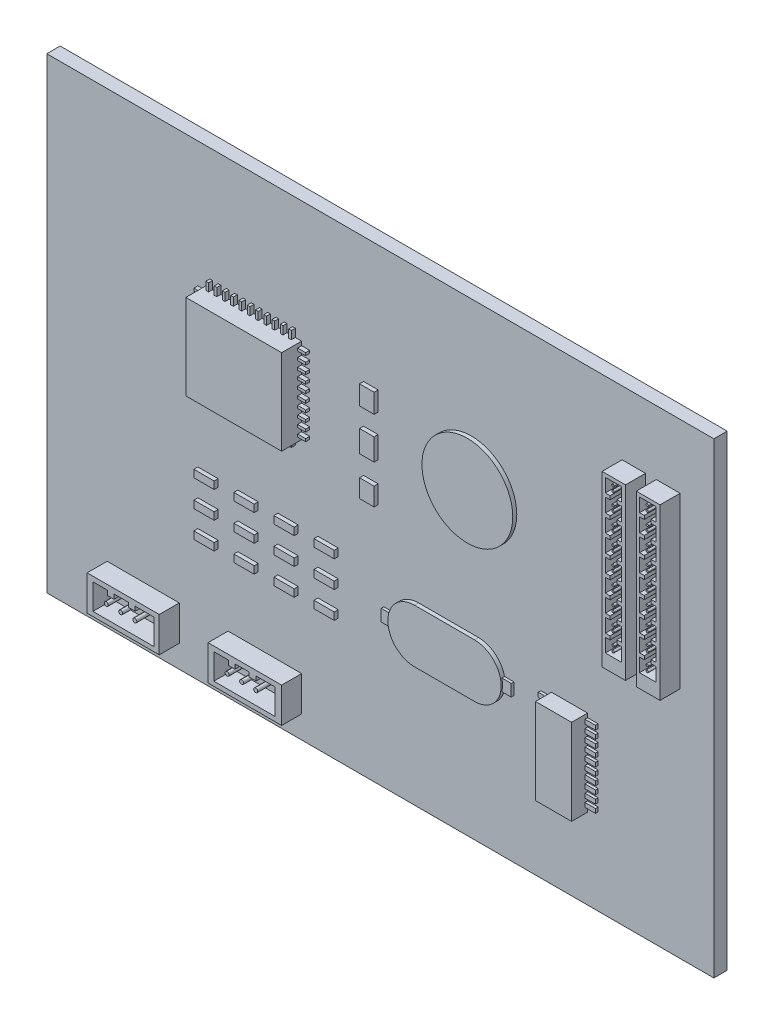
SolidWorks part; units mm, degrees
ref_plane "前视基准面" through (0, 0, 0) normal (0, 0, 1) x (1, 0, 0)
ref_plane "上视基准面" through (0, 0, 0) normal (0, 1, 0) x (1, 0, 0)
ref_plane "右视基准面" through (0, 0, 0) normal (1, 0, 0) x (0, 0, -1)
sketch "草图1" plane through (0, 0, 0) normal (0, 0, 1) x (1, 0, 0)
  line L1 (-25, 17.5) -> (25, 17.5)
  line L2 (-25, 17.5) -> (-25, -17.5)
  line L3 (-25, -17.5) -> (25, -17.5)
  line L4 (25, 17.5) -> (25, -17.5)
  line L5 (-25, 17.5) -> (25, -17.5) construction
  line L6 (-25, -17.5) -> (25, 17.5) construction
  point P0 (0, 0)
  point P5 (25, 0)
  dimension "D1" = 35
  dimension "D2" = 50
extrude "凸台-拉伸1" add sketch "草图1" along normal blind 1
sketch "草图2" plane through (0, 0, 1) normal (0, 0, 1) x (1, 0, 0)
  line L1 (-13.0751, 8.3934) -> (-5.8986, 8.3934)
  line L2 (-13.0751, 8.3934) -> (-13.0751, 1.997)
  line L3 (-13.0751, 1.997) -> (-5.8986, 1.997)
  line L4 (-5.8986, 8.3934) -> (-5.8986, 1.997)
  line L5 (-13.0751, 8.3934) -> (-5.8986, 1.997) construction
  line L6 (-13.0751, 1.997) -> (-5.8986, 8.3934) construction
  line L7 (-20.4774, -13.1874) -> (-15.0714, -13.1874)
  line L8 (-20.4774, -13.1874) -> (-20.4774, -15.8086)
  line L9 (-20.4774, -15.8086) -> (-15.0714, -15.8086)
  line L10 (-15.0714, -13.1874) -> (-15.0714, -15.8086)
  line L11 (-11.4127, -13.1874) -> (-5.8986, -13.1874)
  line L12 (-11.4127, -13.1874) -> (-11.4127, -15.8086)
  line L13 (-11.4127, -15.8086) -> (-5.8986, -15.8086)
  line L14 (-5.8986, -13.1874) -> (-5.8986, -15.8086)
  line L15 (18.1224, 12.6986) -> (19.8759, 12.6986)
  line L16 (18.1224, 12.6986) -> (18.1224, 0)
  line L17 (18.1224, 0) -> (19.8759, 0)
  line L18 (19.8759, 12.6986) -> (19.8759, 0)
  line L19 (20.6852, 12.6986) -> (22.4661, 12.6986)
  line L20 (20.6852, 12.6986) -> (20.6852, 0)
  line L21 (20.6852, 0) -> (22.4661, 0)
  line L22 (22.4661, 12.6986) -> (22.4661, 0)
  point P0 (-9.4869, 5.1952)
extrude "凸台-拉伸2" add sketch "草图2" along normal blind 1.5
sketch "草图3" plane through (0, 0, 1) normal (0, 0, 1) x (1, 0, 0)
  line L0 (-5.8986, 8.3934) -> (-13.0751, 8.3934) construction
  line L1 (-12.7751, 8.3934) -> (-12.5751, 8.3934)
  line L2 (-12.7751, 8.3934) -> (-12.7751, 8.9934)
  line L3 (-12.7751, 8.9934) -> (-12.5751, 8.9934)
  line L4 (-12.5751, 8.3934) -> (-12.5751, 8.9934)
  line L5 (-13.0751, 8.3934) -> (-13.0751, 1.997) construction
  line L6 (-12.1551, 8.9934) -> (-11.9551, 8.9934)
  line L7 (-12.1551, 8.3934) -> (-12.1551, 8.9934)
  line L8 (-11.9551, 8.3934) -> (-11.9551, 8.9934)
  line L9 (-12.1551, 8.3934) -> (-11.9551, 8.3934)
  line L10 (-11.5351, 8.9934) -> (-11.3351, 8.9934)
  line L11 (-11.5351, 8.3934) -> (-11.5351, 8.9934)
  line L12 (-11.3351, 8.3934) -> (-11.3351, 8.9934)
  line L13 (-11.5351, 8.3934) -> (-11.3351, 8.3934)
  line L14 (-10.9151, 8.9934) -> (-10.7151, 8.9934)
  line L15 (-10.9151, 8.3934) -> (-10.9151, 8.9934)
  line L16 (-10.7151, 8.3934) -> (-10.7151, 8.9934)
  line L17 (-10.9151, 8.3934) -> (-10.7151, 8.3934)
  line L18 (-10.2951, 8.9934) -> (-10.0951, 8.9934)
  line L19 (-10.2951, 8.3934) -> (-10.2951, 8.9934)
  line L20 (-10.0951, 8.3934) -> (-10.0951, 8.9934)
  line L21 (-10.2951, 8.3934) -> (-10.0951, 8.3934)
  line L22 (-9.6751, 8.9934) -> (-9.4751, 8.9934)
  line L23 (-9.6751, 8.3934) -> (-9.6751, 8.9934)
  line L24 (-9.4751, 8.3934) -> (-9.4751, 8.9934)
  line L25 (-9.6751, 8.3934) -> (-9.4751, 8.3934)
  line L26 (-9.0551, 8.9934) -> (-8.8551, 8.9934)
  line L27 (-9.0551, 8.3934) -> (-9.0551, 8.9934)
  line L28 (-8.8551, 8.3934) -> (-8.8551, 8.9934)
  line L29 (-9.0551, 8.3934) -> (-8.8551, 8.3934)
  line L30 (-8.4351, 8.9934) -> (-8.2351, 8.9934)
  line L31 (-8.4351, 8.3934) -> (-8.4351, 8.9934)
  line L32 (-8.2351, 8.3934) -> (-8.2351, 8.9934)
  line L33 (-8.4351, 8.3934) -> (-8.2351, 8.3934)
  line L34 (-7.8151, 8.9934) -> (-7.6151, 8.9934)
  line L35 (-7.8151, 8.3934) -> (-7.8151, 8.9934)
  line L36 (-7.6151, 8.3934) -> (-7.6151, 8.9934)
  line L37 (-7.8151, 8.3934) -> (-7.6151, 8.3934)
  line L38 (-7.1951, 8.9934) -> (-6.9951, 8.9934)
  line L39 (-7.1951, 8.3934) -> (-7.1951, 8.9934)
  line L40 (-6.9951, 8.3934) -> (-6.9951, 8.9934)
  line L41 (-7.1951, 8.3934) -> (-6.9951, 8.3934)
  line L42 (-6.5751, 8.9934) -> (-6.3751, 8.9934)
  line L43 (-6.5751, 8.3934) -> (-6.5751, 8.9934)
  line L44 (-6.3751, 8.3934) -> (-6.3751, 8.9934)
  line L45 (-6.5751, 8.3934) -> (-6.3751, 8.3934)
  line L46 (-5.8986, 5.1952) -> (-4.9719, 5.1952) construction
  line L47 (-5.8986, 1.997) -> (-5.8986, 8.3934) construction
  line L48 (-6.5751, 1.997) -> (-6.3751, 1.997)
  line L49 (-6.3751, 1.997) -> (-6.3751, 1.397)
  line L50 (-6.5751, 1.997) -> (-6.5751, 1.397)
  line L51 (-6.5751, 1.397) -> (-6.3751, 1.397)
  line L52 (-7.1951, 1.997) -> (-6.9951, 1.997)
  line L53 (-6.9951, 1.997) -> (-6.9951, 1.397)
  line L54 (-7.1951, 1.997) -> (-7.1951, 1.397)
  line L55 (-7.1951, 1.397) -> (-6.9951, 1.397)
  line L56 (-7.8151, 1.997) -> (-7.6151, 1.997)
  line L57 (-7.6151, 1.997) -> (-7.6151, 1.397)
  line L58 (-7.8151, 1.997) -> (-7.8151, 1.397)
  line L59 (-7.8151, 1.397) -> (-7.6151, 1.397)
  line L60 (-8.4351, 1.997) -> (-8.2351, 1.997)
  line L61 (-8.2351, 1.997) -> (-8.2351, 1.397)
  line L62 (-8.4351, 1.997) -> (-8.4351, 1.397)
  line L63 (-8.4351, 1.397) -> (-8.2351, 1.397)
  line L64 (-9.0551, 1.997) -> (-8.8551, 1.997)
  line L65 (-8.8551, 1.997) -> (-8.8551, 1.397)
  line L66 (-9.0551, 1.997) -> (-9.0551, 1.397)
  line L67 (-9.0551, 1.397) -> (-8.8551, 1.397)
  line L68 (-9.6751, 1.997) -> (-9.4751, 1.997)
  line L69 (-9.4751, 1.997) -> (-9.4751, 1.397)
  line L70 (-9.6751, 1.997) -> (-9.6751, 1.397)
  line L71 (-9.6751, 1.397) -> (-9.4751, 1.397)
  line L72 (-10.2951, 1.997) -> (-10.0951, 1.997)
  line L73 (-10.0951, 1.997) -> (-10.0951, 1.397)
  line L74 (-10.2951, 1.997) -> (-10.2951, 1.397)
  line L75 (-10.2951, 1.397) -> (-10.0951, 1.397)
  line L76 (-10.9151, 1.997) -> (-10.7151, 1.997)
  line L77 (-10.7151, 1.997) -> (-10.7151, 1.397)
  line L78 (-10.9151, 1.997) -> (-10.9151, 1.397)
  line L79 (-10.9151, 1.397) -> (-10.7151, 1.397)
  line L80 (-11.5351, 1.997) -> (-11.3351, 1.997)
  line L81 (-11.3351, 1.997) -> (-11.3351, 1.397)
  line L82 (-11.5351, 1.997) -> (-11.5351, 1.397)
  line L83 (-11.5351, 1.397) -> (-11.3351, 1.397)
  line L84 (-12.1551, 1.997) -> (-11.9551, 1.997)
  line L85 (-11.9551, 1.997) -> (-11.9551, 1.397)
  line L86 (-12.1551, 1.997) -> (-12.1551, 1.397)
  line L87 (-12.1551, 1.397) -> (-11.9551, 1.397)
  line L88 (-12.5751, 1.997) -> (-12.5751, 1.397)
  line L89 (-12.7751, 1.397) -> (-12.5751, 1.397)
  line L90 (-12.7751, 1.997) -> (-12.7751, 1.397)
  line L91 (-12.7751, 1.997) -> (-12.5751, 1.997)
  line L92 (-13.0751, 8.3934) -> (-13.0751, 1.997) construction
  line L93 (-13.0751, 8.0934) -> (-13.6751, 8.0934)
  line L94 (-13.0751, 8.0934) -> (-13.0751, 7.8934)
  line L95 (-13.0751, 7.8934) -> (-13.6751, 7.8934)
  line L96 (-13.6751, 8.0934) -> (-13.6751, 7.8934)
  line L97 (-13.6751, 7.4734) -> (-13.6751, 7.2734)
  line L98 (-13.0751, 7.4734) -> (-13.6751, 7.4734)
  line L99 (-13.0751, 7.2734) -> (-13.6751, 7.2734)
  line L100 (-13.0751, 7.4734) -> (-13.0751, 7.2734)
  line L101 (-13.6751, 6.8534) -> (-13.6751, 6.6534)
  line L102 (-13.0751, 6.8534) -> (-13.6751, 6.8534)
  line L103 (-13.0751, 6.6534) -> (-13.6751, 6.6534)
  line L104 (-13.0751, 6.8534) -> (-13.0751, 6.6534)
  line L105 (-13.6751, 6.2334) -> (-13.6751, 6.0334)
  line L106 (-13.0751, 6.2334) -> (-13.6751, 6.2334)
  line L107 (-13.0751, 6.0334) -> (-13.6751, 6.0334)
  line L108 (-13.0751, 6.2334) -> (-13.0751, 6.0334)
  line L109 (-13.6751, 5.6134) -> (-13.6751, 5.4134)
  line L110 (-13.0751, 5.6134) -> (-13.6751, 5.6134)
  line L111 (-13.0751, 5.4134) -> (-13.6751, 5.4134)
  line L112 (-13.0751, 5.6134) -> (-13.0751, 5.4134)
  line L113 (-13.6751, 4.9934) -> (-13.6751, 4.7934)
  line L114 (-13.0751, 4.9934) -> (-13.6751, 4.9934)
  line L115 (-13.0751, 4.7934) -> (-13.6751, 4.7934)
  line L116 (-13.0751, 4.9934) -> (-13.0751, 4.7934)
  line L117 (-13.6751, 4.3734) -> (-13.6751, 4.1734)
  line L118 (-13.0751, 4.3734) -> (-13.6751, 4.3734)
  line L119 (-13.0751, 4.1734) -> (-13.6751, 4.1734)
  line L120 (-13.0751, 4.3734) -> (-13.0751, 4.1734)
  line L121 (-13.6751, 3.7534) -> (-13.6751, 3.5534)
  line L122 (-13.0751, 3.7534) -> (-13.6751, 3.7534)
  line L123 (-13.0751, 3.5534) -> (-13.6751, 3.5534)
  line L124 (-13.0751, 3.7534) -> (-13.0751, 3.5534)
  line L125 (-13.6751, 3.1334) -> (-13.6751, 2.9334)
  line L126 (-13.0751, 3.1334) -> (-13.6751, 3.1334)
  line L127 (-13.0751, 2.9334) -> (-13.6751, 2.9334)
  line L128 (-13.0751, 3.1334) -> (-13.0751, 2.9334)
  line L129 (-13.6751, 2.5134) -> (-13.6751, 2.3134)
  line L130 (-13.0751, 2.5134) -> (-13.6751, 2.5134)
  line L131 (-13.0751, 2.3134) -> (-13.6751, 2.3134)
  line L132 (-13.0751, 2.5134) -> (-13.0751, 2.3134)
  line L134 (-5.8986, 5.1952) -> (-13.0751, 5.1952) construction
  line L135 (-9.4869, 5.1952) -> (-9.4869, 7.8934) construction
  line L136 (-5.8986, 2.5134) -> (-5.8986, 2.3134)
  line L137 (-5.8986, 2.3134) -> (-5.2986, 2.3134)
  line L138 (-5.8986, 2.5134) -> (-5.2986, 2.5134)
  line L139 (-5.2986, 2.5134) -> (-5.2986, 2.3134)
  line L140 (-5.8986, 3.1334) -> (-5.8986, 2.9334)
  line L141 (-5.8986, 2.9334) -> (-5.2986, 2.9334)
  line L142 (-5.8986, 3.1334) -> (-5.2986, 3.1334)
  line L143 (-5.2986, 3.1334) -> (-5.2986, 2.9334)
  line L144 (-5.8986, 3.7534) -> (-5.8986, 3.5534)
  line L145 (-5.8986, 3.5534) -> (-5.2986, 3.5534)
  line L146 (-5.8986, 3.7534) -> (-5.2986, 3.7534)
  line L147 (-5.2986, 3.7534) -> (-5.2986, 3.5534)
  line L148 (-5.8986, 4.3734) -> (-5.8986, 4.1734)
  line L149 (-5.8986, 4.1734) -> (-5.2986, 4.1734)
  line L150 (-5.8986, 4.3734) -> (-5.2986, 4.3734)
  line L151 (-5.2986, 4.3734) -> (-5.2986, 4.1734)
  line L152 (-5.8986, 4.9934) -> (-5.8986, 4.7934)
  line L153 (-5.8986, 4.7934) -> (-5.2986, 4.7934)
  line L154 (-5.8986, 4.9934) -> (-5.2986, 4.9934)
  line L155 (-5.2986, 4.9934) -> (-5.2986, 4.7934)
  line L156 (-5.8986, 5.6134) -> (-5.8986, 5.4134)
  line L157 (-5.8986, 5.4134) -> (-5.2986, 5.4134)
  line L158 (-5.8986, 5.6134) -> (-5.2986, 5.6134)
  line L159 (-5.2986, 5.6134) -> (-5.2986, 5.4134)
  line L160 (-5.8986, 6.2334) -> (-5.8986, 6.0334)
  line L161 (-5.8986, 6.0334) -> (-5.2986, 6.0334)
  line L162 (-5.8986, 6.2334) -> (-5.2986, 6.2334)
  line L163 (-5.2986, 6.2334) -> (-5.2986, 6.0334)
  line L164 (-5.8986, 6.8534) -> (-5.8986, 6.6534)
  line L165 (-5.8986, 6.6534) -> (-5.2986, 6.6534)
  line L166 (-5.8986, 6.8534) -> (-5.2986, 6.8534)
  line L167 (-5.2986, 6.8534) -> (-5.2986, 6.6534)
  line L168 (-5.8986, 7.4734) -> (-5.8986, 7.2734)
  line L169 (-5.8986, 7.2734) -> (-5.2986, 7.2734)
  line L170 (-5.8986, 7.4734) -> (-5.2986, 7.4734)
  line L171 (-5.2986, 7.4734) -> (-5.2986, 7.2734)
  line L172 (-5.2986, 8.0934) -> (-5.2986, 7.8934)
  line L173 (-5.8986, 7.8934) -> (-5.2986, 7.8934)
  line L174 (-5.8986, 8.0934) -> (-5.8986, 7.8934)
  line L175 (-5.8986, 8.0934) -> (-5.2986, 8.0934)
  line L176 (-10.6751, -3.6643) -> (-10.6751, -4.218)
  line L177 (-13.6751, -3.6643) -> (-12.1551, -3.6643)
  line L178 (-13.6751, -3.6643) -> (-13.6751, -4.218)
  line L179 (-13.6751, -4.218) -> (-12.1551, -4.218)
  line L180 (-12.1551, -3.6643) -> (-12.1551, -4.218)
  line L181 (-10.6751, -3.6643) -> (-9.1551, -3.6643)
  line L182 (-9.1551, -3.6643) -> (-9.1551, -4.218)
  line L183 (-10.6751, -4.218) -> (-9.1551, -4.218)
  line L184 (-7.6751, -3.6643) -> (-7.6751, -4.218)
  line L185 (-7.6751, -3.6643) -> (-6.1551, -3.6643)
  line L186 (-6.1551, -3.6643) -> (-6.1551, -4.218)
  line L187 (-7.6751, -4.218) -> (-6.1551, -4.218)
  line L188 (-4.6751, -3.6643) -> (-4.6751, -4.218)
  line L189 (-4.6751, -3.6643) -> (-3.1551, -3.6643)
  line L190 (-3.1551, -3.6643) -> (-3.1551, -4.218)
  line L191 (-4.6751, -4.218) -> (-3.1551, -4.218)
  line L192 (-10.6751, -5.6643) -> (-10.6751, -6.218)
  line L193 (-10.6751, -5.6643) -> (-9.1551, -5.6643)
  line L194 (-9.1551, -5.6643) -> (-9.1551, -6.218)
  line L195 (-10.6751, -6.218) -> (-9.1551, -6.218)
  line L196 (-7.6751, -5.6643) -> (-7.6751, -6.218)
  line L197 (-7.6751, -5.6643) -> (-6.1551, -5.6643)
  line L198 (-6.1551, -5.6643) -> (-6.1551, -6.218)
  line L199 (-7.6751, -6.218) -> (-6.1551, -6.218)
  line L200 (-4.6751, -5.6643) -> (-4.6751, -6.218)
  line L201 (-4.6751, -5.6643) -> (-3.1551, -5.6643)
  line L202 (-3.1551, -5.6643) -> (-3.1551, -6.218)
  line L203 (-4.6751, -6.218) -> (-3.1551, -6.218)
  line L204 (-10.6751, -7.6643) -> (-10.6751, -8.218)
  line L205 (-10.6751, -7.6643) -> (-9.1551, -7.6643)
  line L206 (-9.1551, -7.6643) -> (-9.1551, -8.218)
  line L207 (-10.6751, -8.218) -> (-9.1551, -8.218)
  line L208 (-7.6751, -7.6643) -> (-7.6751, -8.218)
  line L209 (-7.6751, -7.6643) -> (-6.1551, -7.6643)
  line L210 (-6.1551, -7.6643) -> (-6.1551, -8.218)
  line L211 (-7.6751, -8.218) -> (-6.1551, -8.218)
  line L212 (-4.6751, -7.6643) -> (-4.6751, -8.218)
  line L213 (-4.6751, -7.6643) -> (-3.1551, -7.6643)
  line L214 (-3.1551, -7.6643) -> (-3.1551, -8.218)
  line L215 (-4.6751, -8.218) -> (-3.1551, -8.218)
  line L216 (-13.6751, -5.6643) -> (-13.6751, -6.218)
  line L217 (-13.6751, -5.6643) -> (-12.1551, -5.6643)
  line L218 (-12.1551, -5.6643) -> (-12.1551, -6.218)
  line L219 (-13.6751, -6.218) -> (-12.1551, -6.218)
  line L220 (-13.6751, -7.6643) -> (-13.6751, -8.218)
  line L221 (-13.6751, -7.6643) -> (-12.1551, -7.6643)
  line L222 (-12.1551, -7.6643) -> (-12.1551, -8.218)
  line L223 (-13.6751, -8.218) -> (-12.1551, -8.218)
  line L224 (2.8619, -6.218) -> (7.358, -6.218) construction
  line L225 (2.8619, -8.218) -> (7.358, -8.218)
  line L226 (2.8619, -4.218) -> (7.358, -4.218)
  line L228 (-1.2544, 8.0934) -> (-0.166, 8.0934)
  line L229 (-1.2544, 8.0934) -> (-1.2544, 6.6534)
  line L230 (-1.2544, 6.6534) -> (-0.166, 6.6534)
  line L231 (-0.166, 8.0934) -> (-0.166, 6.6534)
  line L232 (-1.2544, 5.1952) -> (-0.166, 5.1952)
  line L233 (-1.2544, 5.1952) -> (-1.2544, 3.5534)
  line L234 (-1.2544, 3.5534) -> (-0.166, 3.5534)
  line L235 (-0.166, 5.1952) -> (-0.166, 3.5534)
  line L236 (-1.2544, 1.997) -> (-0.166, 1.997)
  line L237 (-1.2544, 1.997) -> (-1.2544, 0.6408)
  line L238 (-1.2544, 0.6408) -> (-0.166, 0.6408)
  line L239 (-0.166, 1.997) -> (-0.166, 0.6408)
  circle A0 centre (6.8237, 5.1952) radius 3.4034
  arc A1 (2.8619, -8.218) -> (2.8619, -4.218) centre (2.8619, -6.218) cw
  arc A2 (7.358, -8.218) -> (7.358, -4.218) centre (7.358, -6.218) ccw
  point P102 (-13.6751, 7.9934)
  point P103 (-13.0751, 7.9934)
  dimension "D11" = 2
  dimension "D1" = 0.2
  dimension "D2" = 0.6
  dimension "D3" = 0.3
  dimension "D5" = 0.2
  dimension "D6" = 0.3
  dimension "D7" = 0.6
  dimension "D9" = 4
  dimension "D10" = 3
  dimension "D12" = 2
  dimension "D4" = 11
  dimension "D8" = 10
extrude "凸台-拉伸3" add sketch "草图3" along normal blind 0.3
sketch "草图4" plane through (0, 0, 2.5) normal (0, 0, 1) x (1, 0, 0)
  line L0 (-18.4668, -13.5527) -> (-17.3908, -13.5527)
  line L1 (-20.0423, -13.5527) -> (-18.959, -13.5527)
  line L2 (-20.0423, -13.5527) -> (-20.0423, -15.4718)
  line L3 (-20.0423, -15.4718) -> (-15.4487, -15.4718)
  line L4 (-15.4487, -13.5527) -> (-15.4487, -15.4718)
  line L5 (-16.8704, -13.5527) -> (-15.4487, -13.5527)
  line L6 (-18.959, -13.5527) -> (-18.959, -13.9041)
  line L7 (-18.959, -13.9041) -> (-18.4668, -13.9041)
  line L8 (-18.4668, -13.5527) -> (-18.4668, -13.9041)
  line L9 (-9.8944, -13.9041) -> (-9.4021, -13.9041)
  line L10 (-17.3908, -13.5527) -> (-17.3908, -13.876)
  line L11 (-17.3908, -13.876) -> (-16.8704, -13.876)
  line L12 (-16.8704, -13.5527) -> (-16.8704, -13.876)
  line L13 (-9.8944, -13.5527) -> (-9.8944, -13.9041)
  line L14 (-9.4021, -13.5527) -> (-9.4021, -13.9041)
  line L15 (-10.9777, -13.5527) -> (-9.8944, -13.5527)
  line L16 (-6.384, -13.5527) -> (-6.384, -15.4718)
  line L17 (-7.8058, -13.5527) -> (-7.8058, -13.876)
  line L18 (-8.3262, -13.876) -> (-7.8058, -13.876)
  line L19 (-10.9777, -13.5527) -> (-10.9777, -15.4718)
  line L20 (-10.9777, -15.4718) -> (-6.384, -15.4718)
  line L21 (-8.3262, -13.5527) -> (-8.3262, -13.876)
  line L22 (-9.4021, -13.5527) -> (-8.3262, -13.5527)
  line L23 (-7.8058, -13.5527) -> (-6.384, -13.5527)
  line L24 (18.368, 10.1195) -> (18.7229, 10.1195)
  line L25 (18.368, 12.4376) -> (19.5826, 12.4376)
  line L26 (18.368, 12.4376) -> (18.368, 11.4195)
  line L27 (18.368, 1.0324) -> (19.5826, 1.0324)
  line L28 (19.5826, 12.4376) -> (19.5826, 11.4195)
  line L29 (18.368, 11.4195) -> (18.7229, 11.4195)
  line L30 (19.5826, 11.1538) -> (19.5826, 10.1195)
  line L31 (18.368, 11.1538) -> (18.7229, 11.1538)
  line L32 (18.7229, 11.4195) -> (18.7229, 11.1538)
  line L33 (19.5826, 11.4195) -> (19.2268, 11.4195)
  line L34 (19.5826, 9.8538) -> (19.5826, 8.8195)
  line L35 (19.5826, 11.1538) -> (19.2268, 11.1538)
  line L36 (19.2268, 11.4195) -> (19.2268, 11.1538)
  line L37 (18.7229, 10.1195) -> (18.7229, 9.8538)
  line L38 (18.368, 9.8538) -> (18.7229, 9.8538)
  line L39 (19.2268, 10.1195) -> (19.2268, 9.8538)
  line L40 (19.5826, 10.1195) -> (19.2268, 10.1195)
  line L41 (19.5826, 9.8538) -> (19.2268, 9.8538)
  line L42 (18.368, 8.8195) -> (18.7229, 8.8195)
  line L43 (18.7229, 8.8195) -> (18.7229, 8.5538)
  line L44 (18.368, 8.5538) -> (18.7229, 8.5538)
  line L45 (19.2268, 8.8195) -> (19.2268, 8.5538)
  line L46 (19.5826, 8.8195) -> (19.2268, 8.8195)
  line L47 (19.5826, 8.5538) -> (19.2268, 8.5538)
  line L48 (18.368, 7.5195) -> (18.7229, 7.5195)
  line L49 (18.7229, 7.5195) -> (18.7229, 7.2538)
  line L50 (18.368, 7.2538) -> (18.7229, 7.2538)
  line L51 (19.2268, 7.5195) -> (19.2268, 7.2538)
  line L52 (19.5826, 7.5195) -> (19.2268, 7.5195)
  line L53 (19.5826, 7.2538) -> (19.2268, 7.2538)
  line L54 (18.368, 6.2195) -> (18.7229, 6.2195)
  line L55 (18.7229, 6.2195) -> (18.7229, 5.9538)
  line L56 (18.368, 5.9538) -> (18.7229, 5.9538)
  line L57 (19.2268, 6.2195) -> (19.2268, 5.9538)
  line L58 (19.5826, 6.2195) -> (19.2268, 6.2195)
  line L59 (19.5826, 5.9538) -> (19.2268, 5.9538)
  line L60 (18.368, 4.9195) -> (18.7229, 4.9195)
  line L61 (18.7229, 4.9195) -> (18.7229, 4.6538)
  line L62 (18.368, 4.6538) -> (18.7229, 4.6538)
  line L63 (19.2268, 4.9195) -> (19.2268, 4.6538)
  line L64 (19.5826, 4.9195) -> (19.2268, 4.9195)
  line L65 (19.5826, 4.6538) -> (19.2268, 4.6538)
  line L66 (18.368, 3.6195) -> (18.7229, 3.6195)
  line L67 (18.7229, 3.6195) -> (18.7229, 3.3538)
  line L68 (18.368, 3.3538) -> (18.7229, 3.3538)
  line L69 (19.2268, 3.6195) -> (19.2268, 3.3538)
  line L70 (19.5826, 3.6195) -> (19.2268, 3.6195)
  line L71 (19.5826, 3.3538) -> (19.2268, 3.3538)
  line L72 (18.368, 2.3195) -> (18.7229, 2.3195)
  line L73 (18.7229, 2.3195) -> (18.7229, 2.0538)
  line L74 (18.368, 2.0538) -> (18.7229, 2.0538)
  line L75 (19.2268, 2.3195) -> (19.2268, 2.0538)
  line L76 (19.5826, 2.3195) -> (19.2268, 2.3195)
  line L77 (19.5826, 2.0538) -> (19.2268, 2.0538)
  line L78 (21.2857, 11.4195) -> (21.2857, 11.1538)
  line L79 (22.1454, 8.8195) -> (21.7896, 8.8195)
  line L80 (21.7896, 7.5195) -> (21.7896, 7.2538)
  line L81 (20.9308, 4.6538) -> (21.2857, 4.6538)
  line L82 (21.7896, 4.9195) -> (21.7896, 4.6538)
  line L83 (20.9308, 2.3195) -> (21.2857, 2.3195)
  line L84 (18.368, 1.0195) -> (18.7229, 1.0195) [skipped]
  line L85 (18.7229, 1.0195) -> (18.7229, 0.7538) [skipped]
  line L86 (18.368, 0.7538) -> (18.7229, 0.7538) [skipped]
  line L87 (19.2268, 1.0195) -> (19.2268, 0.7538) [skipped]
  line L88 (19.5826, 1.0195) -> (19.2268, 1.0195) [skipped]
  line L89 (19.5826, 0.7538) -> (19.2268, 0.7538) [skipped]
  line L90 (21.7896, 11.4195) -> (21.7896, 11.1538)
  line L91 (21.2857, 7.5195) -> (21.2857, 7.2538)
  line L92 (22.1454, 7.5195) -> (21.7896, 7.5195)
  line L93 (20.9308, 5.9538) -> (21.2857, 5.9538)
  line L94 (20.9308, 11.4195) -> (21.2857, 11.4195)
  line L95 (22.1454, 9.8538) -> (21.7896, 9.8538)
  line L96 (21.2857, 6.2195) -> (21.2857, 5.9538)
  line L97 (22.1454, 3.3538) -> (21.7896, 3.3538)
  line L98 (22.1454, 2.3195) -> (21.7896, 2.3195)
  line L99 (20.9308, 1.0324) -> (22.1454, 1.0324)
  line L100 (20.9308, 8.5538) -> (21.2857, 8.5538)
  line L101 (22.1454, 4.6538) -> (21.7896, 4.6538)
  line L102 (22.1454, 10.1195) -> (21.7896, 10.1195)
  line L103 (20.9308, 3.6195) -> (21.2857, 3.6195)
  line L105 (21.2857, 8.8195) -> (21.2857, 8.5538)
  line L106 (20.9308, 7.2538) -> (21.2857, 7.2538)
  line L107 (21.2857, 10.1195) -> (21.2857, 9.8538)
  line L108 (22.1454, 7.2538) -> (21.7896, 7.2538)
  line L109 (21.7896, 6.2195) -> (21.7896, 5.9538)
  line L110 (20.9308, 11.1538) -> (21.2857, 11.1538)
  line L111 (20.9308, 4.9195) -> (21.2857, 4.9195)
  line L112 (21.7896, 2.3195) -> (21.7896, 2.0538)
  line L113 (22.1454, 11.4195) -> (21.7896, 11.4195)
  line L114 (21.7896, 8.8195) -> (21.7896, 8.5538)
  line L115 (21.2857, 3.6195) -> (21.2857, 3.3538)
  line L116 (20.9308, 12.4376) -> (20.9308, 11.4195)
  line L117 (22.1454, 2.0538) -> (21.7896, 2.0538)
  line L118 (20.9308, 11.1538) -> (20.9308, 10.1195)
  line L119 (22.1454, 8.5538) -> (21.7896, 8.5538)
  line L120 (22.1454, 6.2195) -> (21.7896, 6.2195)
  line L121 (21.7896, 3.6195) -> (21.7896, 3.3538)
  line L122 (20.9308, 9.8538) -> (21.2857, 9.8538)
  line L123 (20.9308, 8.8195) -> (21.2857, 8.8195)
  line L124 (21.2857, 4.9195) -> (21.2857, 4.6538)
  line L125 (22.1454, 3.6195) -> (21.7896, 3.6195)
  line L126 (20.9308, 10.1195) -> (21.2857, 10.1195)
  line L127 (22.1454, 11.1538) -> (21.7896, 11.1538)
  line L128 (21.2857, 2.3195) -> (21.2857, 2.0538)
  line L129 (22.1454, 12.4376) -> (22.1454, 11.4195)
  line L130 (20.9308, 6.2195) -> (21.2857, 6.2195)
  line L131 (20.9308, 2.0538) -> (21.2857, 2.0538)
  line L132 (20.9308, 12.4376) -> (22.1454, 12.4376)
  line L133 (20.9308, 7.5195) -> (21.2857, 7.5195)
  line L134 (22.1454, 5.9538) -> (21.7896, 5.9538)
  line L135 (21.7896, 10.1195) -> (21.7896, 9.8538)
  line L136 (22.1454, 4.9195) -> (21.7896, 4.9195)
  line L137 (20.9308, 3.3538) -> (21.2857, 3.3538)
  line L138 (18.368, 11.1538) -> (18.368, 10.1195)
  line L139 (18.368, 9.8538) -> (18.368, 8.8195)
  line L140 (22.1454, 9.8538) -> (22.1454, 8.8195)
  line L141 (20.9308, 9.8538) -> (20.9308, 8.8195)
  line L142 (22.1454, 11.1538) -> (22.1454, 10.1195)
  line L143 (22.1454, 8.5538) -> (22.1454, 7.5195)
  line L144 (20.9308, 8.5538) -> (20.9308, 7.5195)
  line L145 (19.5826, 8.5538) -> (19.5826, 7.5195)
  line L146 (18.368, 8.5538) -> (18.368, 7.5195)
  line L147 (19.5826, 7.2538) -> (19.5826, 6.2195)
  line L148 (18.368, 7.2538) -> (18.368, 6.2195)
  line L149 (19.5826, 5.9538) -> (19.5826, 4.9195)
  line L150 (18.368, 5.9538) -> (18.368, 4.9195)
  line L151 (19.5826, 4.6538) -> (19.5826, 3.6195)
  line L152 (18.368, 4.6538) -> (18.368, 3.6195)
  line L153 (19.5826, 3.3538) -> (19.5826, 2.3195)
  line L154 (18.368, 3.3538) -> (18.368, 2.3195)
  line L155 (19.5826, 2.0538) -> (19.5826, 1.0324)
  line L156 (18.368, 2.0538) -> (18.368, 1.0324)
  line L157 (22.1454, 2.0538) -> (22.1454, 1.0324)
  line L158 (20.9308, 2.0538) -> (20.9308, 1.0324)
  line L159 (20.9308, 3.3538) -> (20.9308, 2.3195)
  line L160 (22.1454, 3.3538) -> (22.1454, 2.3195)
  line L161 (22.1454, 4.6538) -> (22.1454, 3.6195)
  line L162 (20.9308, 4.6538) -> (20.9308, 3.6195)
  line L163 (22.1454, 5.9538) -> (22.1454, 4.9195)
  line L164 (20.9308, 5.9538) -> (20.9308, 4.9195)
  line L165 (22.1454, 7.2538) -> (22.1454, 6.2195)
  line L166 (20.9308, 7.2538) -> (20.9308, 6.2195)
  circle A0 centre (-19.0434, -14.4948) radius 0.15
  circle A1 centre (-17.9604, -14.4948) radius 0.15
  circle A2 centre (-16.9056, -14.4948) radius 0.15
  circle A3 centre (-9.9788, -14.4948) radius 0.15
  circle A4 centre (-8.8958, -14.4948) radius 0.15
  circle A5 centre (-7.8409, -14.4948) radius 0.15
  circle A6 centre (18.9408, 12.2001) radius 0.0853
  circle A7 centre (18.9408, 11.8044) radius 0.0853
  circle A8 centre (18.9408, 10.9001) radius 0.0853
  circle A9 centre (18.9408, 10.5044) radius 0.0853
  circle A10 centre (18.9408, 9.6001) radius 0.0853
  circle A11 centre (18.9408, 9.2044) radius 0.0853
  circle A12 centre (18.9408, 8.3001) radius 0.0853
  circle A13 centre (18.9408, 7.9044) radius 0.0853
  circle A14 centre (18.9408, 7.0001) radius 0.0853
  circle A15 centre (18.9408, 6.6044) radius 0.0853
  circle A16 centre (18.9408, 5.7001) radius 0.0853
  circle A17 centre (18.9408, 5.3044) radius 0.0853
  circle A18 centre (18.9408, 4.4001) radius 0.0853
  circle A19 centre (18.9408, 4.0044) radius 0.0853
  circle A20 centre (18.9408, 3.1001) radius 0.0853
  circle A21 centre (18.9408, 2.7044) radius 0.0853
  circle A22 centre (18.9408, 1.8001) radius 0.0853
  circle A23 centre (18.9408, 1.4044) radius 0.0853
  circle A24 centre (21.5036, 10.5044) radius 0.0853
  circle A25 centre (21.5036, 1.8001) radius 0.0853
  circle A26 centre (21.5036, 11.8044) radius 0.0853
  circle A27 centre (21.5036, 7.0001) radius 0.0853
  circle A28 centre (21.5036, 9.2044) radius 0.0853
  circle A29 centre (21.5036, 9.6001) radius 0.0853
  circle A30 centre (21.5036, 6.6044) radius 0.0853
  circle A31 centre (21.5036, 1.4044) radius 0.0853
  circle A32 centre (21.5036, 12.2001) radius 0.0853
  circle A33 centre (21.5036, 5.3044) radius 0.0853
  circle A34 centre (21.5036, 5.7001) radius 0.0853
  circle A35 centre (21.5036, 4.4001) radius 0.0853
  circle A36 centre (21.5036, 10.9001) radius 0.0853
  circle A37 centre (21.5036, 3.1001) radius 0.0853
  circle A38 centre (21.5036, 4.0044) radius 0.0853
  circle A39 centre (21.5036, 2.7044) radius 0.0853
  circle A40 centre (21.5036, 8.3001) radius 0.0853
  circle A41 centre (21.5036, 7.9044) radius 0.0853
  dimension "D1" = 0.3
  dimension "D2" = 0.3
  dimension "D3" = 9
extrude "切除-拉伸1" cut sketch "草图4" against normal blind 1.5
sketch "草图5" plane through (0, 0, 1) normal (0, 0, 1) x (1, 0, 0)
  line L1 (12.8266, -5.035) -> (15.5351, -5.035)
  line L2 (12.8266, -5.035) -> (12.8266, -11.4677)
  line L3 (12.8266, -11.4677) -> (15.5351, -11.4677)
  line L4 (15.5351, -5.035) -> (15.5351, -11.4677)
extrude "凸台-拉伸4" add sketch "草图5" along normal blind 1.2
sketch "草图6" plane through (0, 0, 1) normal (0, 0, 1) x (1, 0, 0)
  line L0 (15.5351, -11.4677) -> (15.5351, -5.035) construction
  line L1 (15.5351, -5.3347) -> (16.3281, -5.3347)
  line L2 (15.5351, -5.3347) -> (15.5351, -5.6522)
  line L3 (15.5351, -5.6522) -> (16.3281, -5.6522)
  line L4 (16.3281, -5.3347) -> (16.3281, -5.6522)
  line L5 (15.5351, -5.9347) -> (15.5351, -6.2522)
  line L6 (15.5351, -5.9347) -> (16.3281, -5.9347)
  line L7 (16.3281, -5.9347) -> (16.3281, -6.2522)
  line L8 (15.5351, -6.2522) -> (16.3281, -6.2522)
  line L9 (15.5351, -6.5347) -> (15.5351, -6.8522)
  line L10 (15.5351, -6.5347) -> (16.3281, -6.5347)
  line L11 (16.3281, -6.5347) -> (16.3281, -6.8522)
  line L12 (15.5351, -6.8522) -> (16.3281, -6.8522)
  line L13 (15.5351, -7.1347) -> (15.5351, -7.4522)
  line L14 (15.5351, -7.1347) -> (16.3281, -7.1347)
  line L15 (16.3281, -7.1347) -> (16.3281, -7.4522)
  line L16 (15.5351, -7.4522) -> (16.3281, -7.4522)
  line L17 (15.5351, -7.7347) -> (15.5351, -8.0522)
  line L18 (15.5351, -7.7347) -> (16.3281, -7.7347)
  line L19 (16.3281, -7.7347) -> (16.3281, -8.0522)
  line L20 (15.5351, -8.0522) -> (16.3281, -8.0522)
  line L21 (15.5351, -8.3347) -> (15.5351, -8.6522)
  line L22 (15.5351, -8.3347) -> (16.3281, -8.3347)
  line L23 (16.3281, -8.3347) -> (16.3281, -8.6522)
  line L24 (15.5351, -8.6522) -> (16.3281, -8.6522)
  line L25 (15.5351, -8.9347) -> (15.5351, -9.2522)
  line L26 (15.5351, -8.9347) -> (16.3281, -8.9347)
  line L27 (16.3281, -8.9347) -> (16.3281, -9.2522)
  line L28 (15.5351, -9.2522) -> (16.3281, -9.2522)
  line L29 (15.5351, -9.5347) -> (15.5351, -9.8522)
  line L30 (15.5351, -9.5347) -> (16.3281, -9.5347)
  line L31 (16.3281, -9.5347) -> (16.3281, -9.8522)
  line L32 (15.5351, -9.8522) -> (16.3281, -9.8522)
  line L33 (15.5351, -10.1347) -> (15.5351, -10.4522)
  line L34 (15.5351, -10.1347) -> (16.3281, -10.1347)
  line L35 (16.3281, -10.1347) -> (16.3281, -10.4522)
  line L36 (15.5351, -10.4522) -> (16.3281, -10.4522)
  line L37 (15.5351, -10.7347) -> (15.5351, -11.0522)
  line L38 (15.5351, -10.7347) -> (16.3281, -10.7347)
  line L39 (16.3281, -10.7347) -> (16.3281, -11.0522)
  line L40 (15.5351, -11.0522) -> (16.3281, -11.0522)
  line L42 (14.1808, -5.035) -> (14.1808, -6.5347) construction
  line L43 (15.5351, -5.035) -> (12.8266, -5.035) construction
  line L44 (12.8266, -11.0522) -> (12.0335, -11.0522)
  line L45 (12.0335, -10.7347) -> (12.0335, -11.0522)
  line L46 (12.8266, -10.7347) -> (12.0335, -10.7347)
  line L47 (12.8266, -10.7347) -> (12.8266, -11.0522)
  line L48 (12.8266, -10.4522) -> (12.0335, -10.4522)
  line L49 (12.0335, -10.1347) -> (12.0335, -10.4522)
  line L50 (12.8266, -10.1347) -> (12.0335, -10.1347)
  line L51 (12.8266, -10.1347) -> (12.8266, -10.4522)
  line L52 (12.8266, -9.8522) -> (12.0335, -9.8522)
  line L53 (12.0335, -9.5347) -> (12.0335, -9.8522)
  line L54 (12.8266, -9.5347) -> (12.0335, -9.5347)
  line L55 (12.8266, -9.5347) -> (12.8266, -9.8522)
  line L56 (12.8266, -9.2522) -> (12.0335, -9.2522)
  line L57 (12.0335, -8.9347) -> (12.0335, -9.2522)
  line L58 (12.8266, -8.9347) -> (12.0335, -8.9347)
  line L59 (12.8266, -8.9347) -> (12.8266, -9.2522)
  line L60 (12.8266, -8.6522) -> (12.0335, -8.6522)
  line L61 (12.0335, -8.3347) -> (12.0335, -8.6522)
  line L62 (12.8266, -8.3347) -> (12.0335, -8.3347)
  line L63 (12.8266, -8.3347) -> (12.8266, -8.6522)
  line L64 (12.8266, -8.0522) -> (12.0335, -8.0522)
  line L65 (12.0335, -7.7347) -> (12.0335, -8.0522)
  line L66 (12.8266, -7.7347) -> (12.0335, -7.7347)
  line L67 (12.8266, -7.7347) -> (12.8266, -8.0522)
  line L68 (12.8266, -7.4522) -> (12.0335, -7.4522)
  line L69 (12.0335, -7.1347) -> (12.0335, -7.4522)
  line L70 (12.8266, -7.1347) -> (12.0335, -7.1347)
  line L71 (12.8266, -7.1347) -> (12.8266, -7.4522)
  line L72 (12.8266, -6.8522) -> (12.0335, -6.8522)
  line L73 (12.0335, -6.5347) -> (12.0335, -6.8522)
  line L74 (12.8266, -6.5347) -> (12.0335, -6.5347)
  line L75 (12.8266, -6.5347) -> (12.8266, -6.8522)
  line L76 (12.8266, -6.2522) -> (12.0335, -6.2522)
  line L77 (12.0335, -5.9347) -> (12.0335, -6.2522)
  line L78 (12.8266, -5.9347) -> (12.0335, -5.9347)
  line L79 (12.8266, -5.9347) -> (12.8266, -6.2522)
  line L80 (12.0335, -5.3347) -> (12.0335, -5.6522)
  line L81 (12.8266, -5.6522) -> (12.0335, -5.6522)
  line L82 (12.8266, -5.3347) -> (12.8266, -5.6522)
  line L83 (12.8266, -5.3347) -> (12.0335, -5.3347)
  line L85 (9.3073, -5.7703) -> (10.0099, -5.7703)
  line L86 (9.3073, -5.7703) -> (9.3073, -6.6607)
  line L87 (9.3073, -6.6607) -> (10.0099, -6.6607)
  line L88 (10.0099, -5.7703) -> (10.0099, -6.6607)
  line L89 (1.1062, -5.7703) -> (0.2663, -5.7703)
  line L90 (1.1062, -5.7703) -> (1.1062, -6.6607)
  line L91 (1.1062, -6.6607) -> (0.2663, -6.6607)
  line L92 (0.2663, -5.7703) -> (0.2663, -6.6607)
  arc A0 (7.358, -8.218) -> (7.358, -4.218) centre (7.358, -6.218) ccw construction
  dimension "D1" = 10
extrude "凸台-拉伸5" add sketch "草图6" along normal blind 0.2
